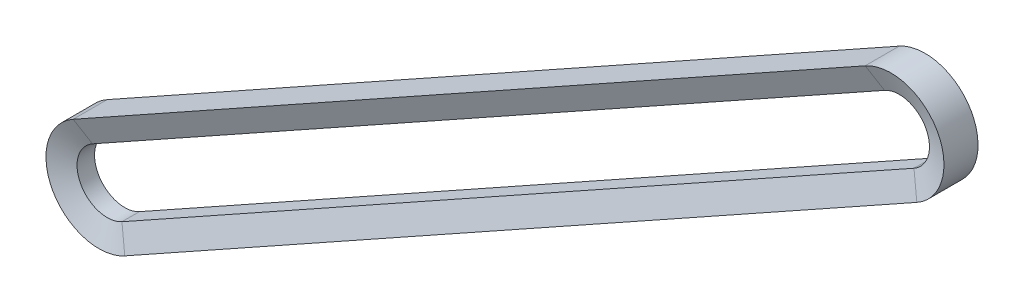
SolidWorks part; units mm, degrees
ref_plane "前视基准面" through (0, 0, 0) normal (0, 0, 1) x (1, 0, 0)
ref_plane "上视基准面" through (0, 0, 0) normal (0, 1, 0) x (1, 0, 0)
ref_plane "右视基准面" through (0, 0, 0) normal (1, 0, 0) x (0, 0, -1)
sketch "草图2" plane through (0, 0, 0) normal (0, 0, 1) x (1, 0, 0)
  line L0 (0, 0) -> (1, 0) construction
  line L1 (0, 0) -> (0, 1) construction
  line L2 (2.5843, -4.6273) -> (-136.4846, -82.2949)
  line L3 (-141.6531, -73.0403) -> (-2.5843, 4.6273)
  arc A0 (-2.5843, 4.6273) -> (2.5843, -4.6273) centre (0, 0) cw
  arc A1 (-136.4846, -82.2949) -> (-141.6531, -73.0403) centre (-139.0689, -77.6676) cw
ref_plane "基准面4" through (0, 0, 0) normal (0.8731, 0.4876, 0) x (0, 0, -1)
sketch "草图3" plane through (0, 0, 0) normal (0.8731, 0.4876, 0) x (0, 0, -1)
  line L0 (-1.535, 5.3) -> (1.535, 5.3)
  line L1 (0, 5.3) -> (0, -5.3) construction
  line L2 (1.535, 5.3) -> (2.9909, 9.3)
  line L3 (2.9909, 9.3) -> (-2.9909, 9.3)
  line L4 (0, 9.3) -> (0, 5.3)
  line L5 (-1.535, 5.3) -> (-2.9909, 9.3)
  dimension "D1" = 110
  dimension "D2" = 4
sweep "扫描1" add profiles "草图3" path "草图2"
